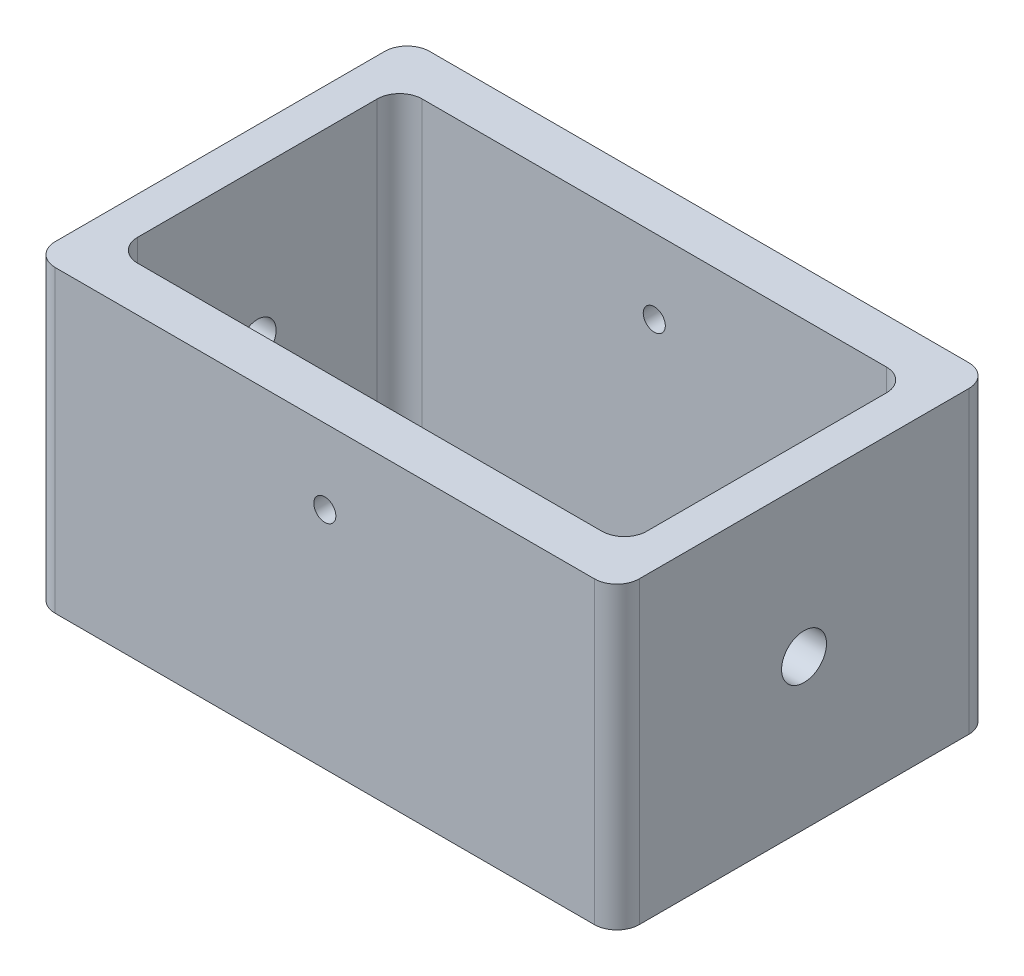
SolidWorks part; units mm, degrees
ref_plane "Front Plane" through (0, 0, 0) normal (0, 0, 1) x (1, 0, 0)
ref_plane "Top Plane" through (0, 0, 0) normal (0, 1, 0) x (1, 0, 0)
ref_plane "Right Plane" through (0, 0, 0) normal (1, 0, 0) x (0, 0, -1)
sketch "Sketch1" plane through (0, 0, 0) normal (0, 1, 0) x (1, 0, 0)
  line L0 (-14.4186, -19.7962) -> (-14.4186, 30.2038)
  line L1 (-14.4186, 30.2038) -> (63.5814, 30.2038)
  line L2 (63.5814, 30.2038) -> (63.5814, -19.7962)
  line L3 (63.5814, -19.7962) -> (-14.4186, -19.7962)
  line L4 (-9.4186, 24.2038) -> (-9.4186, -13.7962)
  line L5 (-9.4186, -13.7962) -> (58.5814, -13.7962)
  line L6 (58.5814, -13.7962) -> (58.5814, 24.2038)
  line L7 (58.5814, 24.2038) -> (-9.4186, 24.2038)
  dimension "D1" = 50
  dimension "D2" = 78
  dimension "D3" = 6
  dimension "D4" = 6
  dimension "D5" = 5
  dimension "D6" = 5
extrude "Boss-Extrude1" add sketch "Sketch1" along normal blind 40
fillet "Fillet1" radius 3 8 edges at (63.5814, 20, -30.2038) (-14.4186, 20, -30.2038) (-14.4186, 20, 19.7962) (58.5814, 20, -24.2038) (-9.4186, 20, -24.2038) (-9.4186, 20, 13.7962) (58.5814, 20, 13.7962) (63.5814, 20, 19.7962)
sketch "Sketch2" plane through (63.5814, 0, 0) normal (1, 0, 0) x (0, 0, -1)
  line L0 (-16.7962, 40) -> (27.2038, 0) construction
  line L1 (-16.7962, 0) -> (27.2038, 40) construction
  circle A0 centre (5.2038, 20) radius 3
  dimension "D1" = 6
extrude "Cut-Extrude1" cut sketch "Sketch2" against normal blind 40
sketch "Sketch3" plane through (-14.4186, 0, 0) normal (-1, 0, 0) x (0, 0, 1)
  circle A0 centre (-5.2038, 20) radius 2.5
  dimension "D1" = 5
extrude "Cut-Extrude2" cut sketch "Sketch3" against normal blind 40
sketch "Sketch4" plane through (0, 0, -30.2038) normal (0, 0, -1) x (-1, 0, 0)
  line L0 (-24.5814, 40) -> (-24.5814, 30) construction
  line L1 (-60.5814, 40) -> (11.4186, 40) construction
  circle A0 centre (-24.5814, 30) radius 1.475
  dimension "D2" = 2.95
  dimension "D1" = 10
extrude "Cut-Extrude3" cut sketch "Sketch4" against normal blind 50
